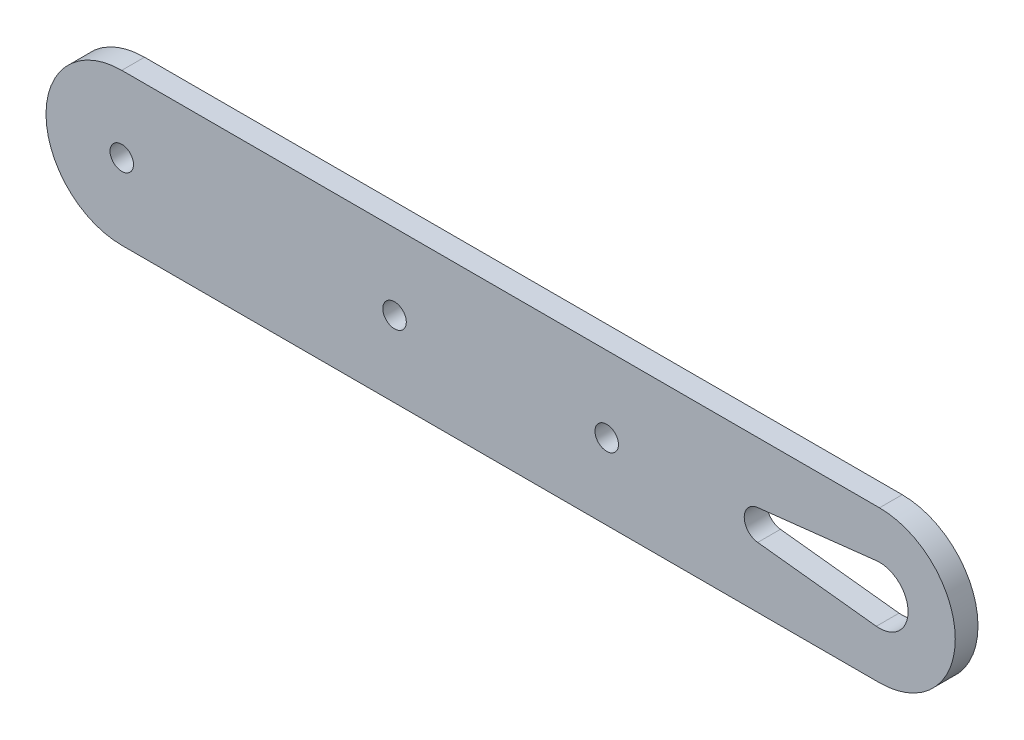
SolidWorks part; units mm, degrees
ref_plane "Front Plane" through (0, 0, 0) normal (0, 0, 1) x (1, 0, 0)
ref_plane "Top Plane" through (0, 0, 0) normal (0, 1, 0) x (1, 0, 0)
ref_plane "Right Plane" through (0, 0, 0) normal (1, 0, 0) x (0, 0, -1)
sketch "Sketch1" plane through (0, 0, 0) normal (0, 0, 1) x (1, 0, 0)
  line L0 (-58.0586, 14.1911) -> (41.9414, 14.1911) construction
  line L1 (-58.0586, 24.1911) -> (41.9414, 24.1911)
  line L2 (-58.0586, 4.1911) -> (41.9414, 4.1911)
  arc A0 (-58.0586, 24.1911) -> (-58.0586, 4.1911) centre (-58.0586, 14.1911) ccw
  arc A1 (41.9414, 4.1911) -> (41.9414, 24.1911) centre (41.9414, 14.1911) ccw
  point P2 (-8.0586, 14.1911)
extrude "Boss-Extrude1" add sketch "Sketch1" along normal blind 3
sketch "Sketch2" plane through (0, 0, 3) normal (0, 0, 1) x (1, 0, 0)
  line L1 (41.5203, 17.9411) -> (25.8703, 16.1836)
  line L2 (41.5203, 10.4411) -> (25.8703, 12.1986)
  arc A1 (41.5203, 17.9411) -> (41.5203, 10.4411) centre (41.9414, 14.1911) cw
  arc A2 (25.8703, 16.1836) -> (25.8703, 12.1986) centre (26.094, 14.1911) ccw
  arc A3 (41.9414, 4.1911) -> (41.9414, 24.1911) centre (41.9414, 14.1911) ccw construction
  dimension "D1" = 7.5
  dimension "D2" = 3.985
  dimension "D3" = 15.65
  dimension "D4" = 15.65
extrude "Cut-Extrude1" cut sketch "Sketch2" against normal blind 3
sketch "Sketch3" plane through (0, 0, 3) normal (0, 0, 1) x (1, 0, 0)
  circle A0 centre (-58.0586, 14.1911) radius 1.55
  arc A1 (-58.0586, 24.1911) -> (-58.0586, 4.1911) centre (-58.0586, 14.1911) ccw construction
extrude "Cut-Extrude2" cut sketch "Sketch3" against normal blind 3 contours A0
sketch "Sketch4" plane through (9.9795, 1.4333, 3) normal (0, 0, 1) x (1, 0, 0)
  line L0 (-68.0381, 2.7578) -> (31.9619, 2.7578) construction
  circle A0 centre (-4.0381, 12.7578) radius 1.55
  arc A2 (31.9619, 2.7578) -> (31.9619, 22.7578) centre (31.9619, 12.7578) ccw construction
  dimension "D1" = 10
  dimension "D2" = 36
extrude "Cut-Extrude4" cut sketch "Sketch4" against normal blind 3
sketch "Sketch5" plane through (-9.9795, 1.4333, 0) normal (0, 0, -1) x (-1, 0, 0)
  line L0 (-51.9208, 22.7578) -> (48.0792, 22.7578) construction
  circle A0 centre (12.0792, 12.7578) radius 1.55
  arc A2 (48.0792, 2.7578) -> (48.0792, 22.7578) centre (48.0792, 12.7578) ccw construction
  dimension "D1" = 10
  dimension "D2" = 36
extrude "Cut-Extrude6" cut sketch "Sketch5" against normal blind 3
